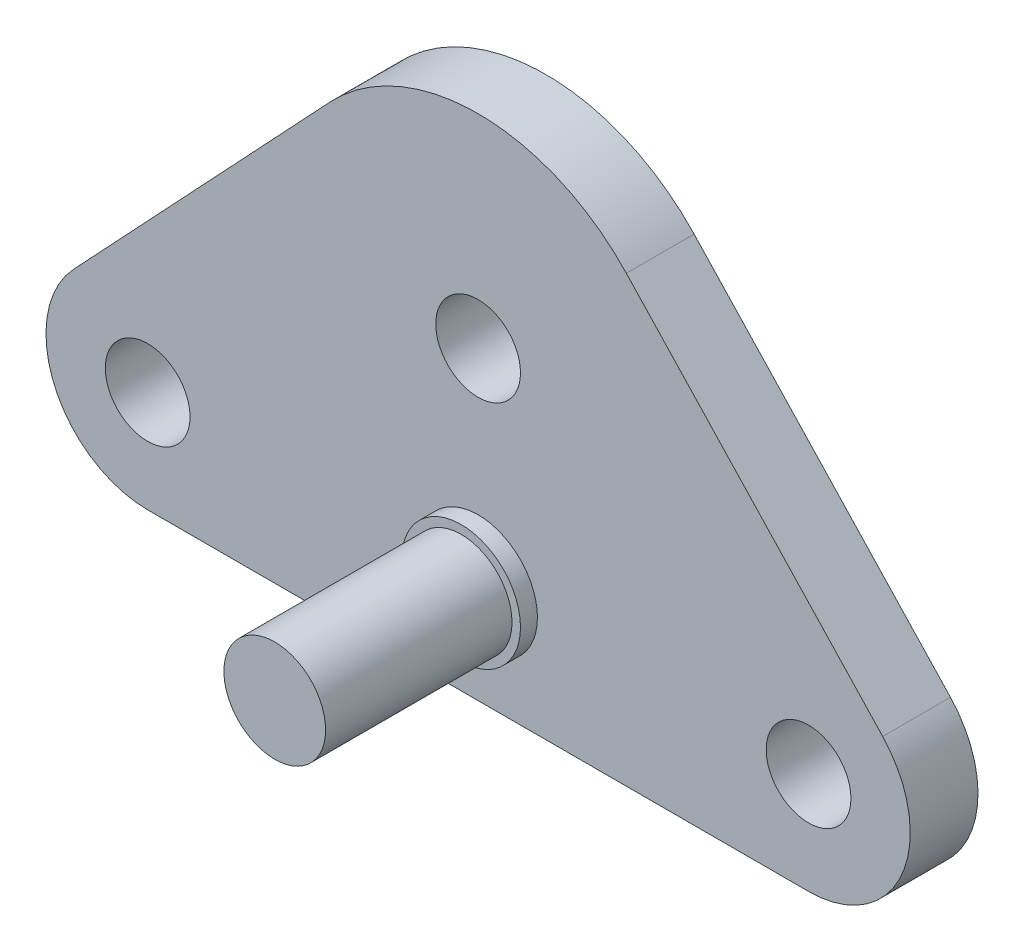
SolidWorks part; units mm, degrees
ref_plane "Plan de face" through (0, 0, 0) normal (0, 0, 1) x (1, 0, 0)
ref_plane "Plan de dessus" through (0, 0, 0) normal (0, 1, 0) x (1, 0, 0)
ref_plane "Plan de droite" through (0, 0, 0) normal (1, 0, 0) x (0, 0, -1)
sketch "Esquisse1" plane through (0, 0, 0) normal (0, 0, 1) x (1, 0, 0)
  line L0 (9.75, -3) -> (-9.75, -3)
  line L1 (-4.3738, 10.1073) -> (-11.9369, 2.0537)
  line L2 (4.3738, 10.1073) -> (11.9369, 2.0537)
  circle A0 centre (0, 6) radius 1.25
  circle A1 centre (9.75, 0) radius 1.25
  circle A2 centre (-9.75, 0) radius 1.25
  arc A3 (-11.9369, 2.0537) -> (-9.75, -3) centre (-9.75, 0) ccw
  arc A4 (-4.3738, 10.1073) -> (4.3738, 10.1073) centre (0, 6) cw
  arc A5 (11.9369, 2.0537) -> (9.75, -3) centre (9.75, 0) cw
  point P9 (0, 0)
  point P10 (-10.0784, -2.8481)
  point P11 (0, 0)
  point P12 (0, 0)
  point P14 (-4.1864, 11.1883)
  point P19 (-12.338, 1.8386)
  point P20 (-6.0289, 11.185)
  point P21 (0, 0)
  point P22 (0, 0)
  point P23 (0, 6)
  point P24 (9.75, 0.9308)
  point P25 (0, 0)
  point P26 (0, 0)
  point P27 (0, 0)
  dimension "D1" = 2.5
  dimension "D2" = 2.5
  dimension "D3" = 2.5
  dimension "D4" = 19.5
  dimension "D7" = 3
  dimension "D8" = 3
  dimension "D9" = 6
  dimension "D5" = 9.75
  dimension "D6" = 6
extrude "Boss.-Extru.1" add sketch "Esquisse1" along normal blind 2
sketch "Esquisse2" plane through (0, 0, 2) normal (0, 0, 1) x (1, 0, 0)
  circle A0 centre (0, 0) radius 1.5
  dimension "D1" = 3
extrude "Boss.-Extru.2" add sketch "Esquisse2" along normal blind 6 contours A0
sketch "Esquisse3" plane through (0, 0, 2) normal (0, 0, 1) x (1, 0, 0)
  circle A0 centre (0, 0) radius 1.75
  dimension "D1" = 3.5
extrude "Boss.-Extru.3" add sketch "Esquisse3" along normal blind 0.5
